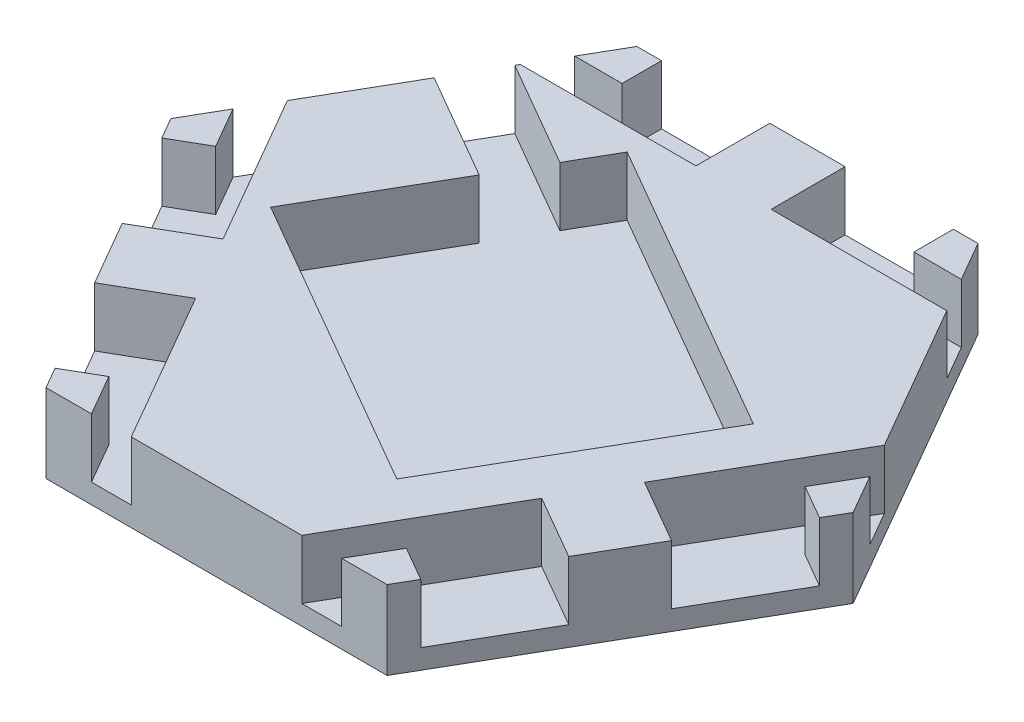
SolidWorks part; units mm, degrees
ref_plane "Front Plane" through (0, 0, 0) normal (0, 0, 1) x (1, 0, 0)
ref_plane "Top Plane" through (0, 0, 0) normal (0, 1, 0) x (1, 0, 0)
ref_plane "Right Plane" through (0, 0, 0) normal (1, 0, 0) x (0, 0, -1)
sketch "Sketch1" plane through (0, 0, 0) normal (0, 1, 0) x (1, 0, 0)
  line L0 (0, 0) -> (39.7226, 0) construction
  line L1 (0, 0) -> (0, 31.3322) construction
  line L3 (69.282, 0) -> (34.641, 60)
  line L4 (34.641, 60) -> (-34.641, 60)
  line L5 (-34.641, 60) -> (-69.282, 0)
  line L6 (-69.282, 0) -> (-34.641, -60)
  line L7 (-34.641, -60) -> (34.641, -60)
  line L8 (34.641, -60) -> (69.282, 0)
  circle A1 centre (0, 0) radius 60 construction
  dimension "D1" = 120
extrude "Boss-Extrude1" add sketch "Sketch1" along normal blind 16
sketch "Sketch2" plane through (0, 16, 0) normal (0, 1, 0) x (1, 0, 0)
  line L0 (-29.641, 60) -> (-29.641, 45)
  line L1 (34.641, 60) -> (-34.641, 60) construction
  line L2 (-29.641, 45) -> (-7.641, 45)
  line L3 (-7.641, 45) -> (-7.641, 60)
  line L4 (7.641, 60) -> (7.641, 45)
  line L5 (7.641, 45) -> (29.641, 45)
  line L6 (29.641, 45) -> (29.641, 60)
  line L7 (66.782, -4.3301) -> (53.7917, 3.1699)
  line L8 (53.7917, 3.1699) -> (42.7917, -15.8827)
  line L9 (42.7917, -15.8827) -> (55.782, -23.3827)
  line L10 (48.141, -36.6173) -> (35.1506, -29.1173)
  line L11 (35.1506, -29.1173) -> (24.1506, -48.1699)
  line L12 (24.1506, -48.1699) -> (37.141, -55.6699)
  line L13 (-37.141, -55.6699) -> (-24.1506, -48.1699)
  line L14 (-24.1506, -48.1699) -> (-35.1506, -29.1173)
  line L15 (-35.1506, -29.1173) -> (-48.141, -36.6173)
  line L16 (-55.782, -23.3827) -> (-42.7917, -15.8827)
  line L17 (-42.7917, -15.8827) -> (-53.7917, 3.1699)
  line L18 (-53.7917, 3.1699) -> (-66.782, -4.3301)
  line L19 (-29.641, 60) -> (-7.641, 60)
  line L20 (7.641, 60) -> (29.641, 60)
  line L21 (66.782, -4.3301) -> (55.782, -23.3827)
  line L22 (48.141, -36.6173) -> (37.141, -55.6699)
  line L23 (-48.141, -36.6173) -> (-37.141, -55.6699)
  line L24 (-66.782, -4.3301) -> (-55.782, -23.3827)
  point P10 (-7.641, 52.5)
  point P11 (29.641, 52.5)
  dimension "D1" = 5
  dimension "D2" = 5
  dimension "D3" = 22
  dimension "D4" = 22
  dimension "D5" = 15
  dimension "D6" = 15
  dimension "D7" = 3
extrude "Cut-Extrude1" cut sketch "Sketch2" against normal blind 12
sketch "Sketch3" plane through (0, 16, 0) normal (0, 1, 0) x (1, 0, 0)
  line L0 (0, 0) -> (-51.9615, 30) construction
  line L1 (-43.5609, -5.4497) -> (17.0609, -40.4497)
  line L2 (-0.0025, 0.0015) -> (34.6385, 60.0015)
  line L3 (-43.5609, -5.4497) -> (-17.0609, 40.4497)
  line L4 (17.0609, -40.4497) -> (43.5609, 5.4497)
  line L5 (-17.0609, 40.4497) -> (43.5609, 5.4497)
  line L6 (-43.5609, -5.4497) -> (43.5609, 5.4497) construction
  line L7 (17.0609, -40.4497) -> (-17.0609, 40.4497) construction
  line L8 (-22.0609, 31.7894) -> (-28.0609, 21.3971)
  line L9 (-22.0609, 31.7894) -> (-43.7115, 44.2894)
  line L10 (-28.0609, 21.3971) -> (-49.7115, 33.8971)
  line L11 (-43.7115, 44.2894) -> (-49.7115, 33.8971)
  line L12 (-34.641, 60) -> (-69.282, 0) construction
  point P4 (0, 0)
  line M19 (-34.641, 60) -> (-69.282, 0)
  dimension "D1" = 70
  dimension "D2" = 53
  dimension "D3" = 10
  dimension "D4" = 12
extrude "Cut-Extrude2" cut sketch "Sketch3" against normal up to vertex (12 mm away) and the other way through all contours L5 L3 L1 L2 | L5 L2 L1 L4 | L10 L3 L9 M19
sketch "Sketch4" plane through (0, 16, 0) normal (0, 1, 0) x (1, 0, 0)
  line L0 (-53.7917, 3.1699) -> (-59.8538, -0.3301)
  line L1 (-53.7917, 3.1699) -> (-66.782, -4.3301) construction
  line L2 (-59.8538, -0.3301) -> (-64.6632, 8)
  line L3 (-49.7115, 33.8971) -> (-69.282, 0) construction
  line L4 (-64.6632, 8) -> (-60.6218, 15)
  line L5 (-60.6218, 15) -> (-53.7917, 3.1699)
  line L6 (-24.1506, -48.1699) -> (-30.2128, -51.6699)
  line L7 (-37.141, -55.6699) -> (-24.1506, -48.1699) construction
  line L8 (-30.2128, -51.6699) -> (-25.4034, -60)
  line L9 (-34.641, -60) -> (34.641, -60) construction
  line L10 (-25.4034, -60) -> (-17.3205, -60)
  line L11 (-17.3205, -60) -> (-24.1506, -48.1699)
  line L12 (43.3013, 45) -> (29.641, 45)
  line L13 (29.641, 45) -> (29.641, 52)
  line L14 (29.641, 52) -> (39.2598, 52)
  line L15 (39.2598, 52) -> (43.3013, 45)
  line L16 (-43.3013, 45) -> (-29.641, 45)
  line L17 (-29.641, 45) -> (-29.641, 52)
  line L18 (-29.641, 52) -> (-39.2598, 52)
  line L19 (-39.2598, 52) -> (-43.3013, 45)
  line L20 (17.3205, -60) -> (24.1506, -48.1699)
  line L21 (24.1506, -48.1699) -> (30.2128, -51.6699)
  line L22 (30.2128, -51.6699) -> (25.4034, -60)
  line L23 (25.4034, -60) -> (17.3205, -60)
  line L24 (60.6218, 15) -> (53.7917, 3.1699)
  line L25 (53.7917, 3.1699) -> (59.8538, -0.3301)
  line L26 (59.8538, -0.3301) -> (64.6632, 8)
  line L27 (64.6632, 8) -> (60.6218, 15)
  point P36 (0, 0)
  dimension "D1" = 7
  dimension "D2" = 3
extrude "Cut-Extrude4" cut sketch "Sketch4" against normal up to vertex (12 mm away)
equation "\"D2@Sketch2\"=\"D1@Sketch2\""
equation "\"D4@Sketch2\"=\"D3@Sketch2\""
equation "\"D6@Sketch2\"=\"D5@Sketch2\""
